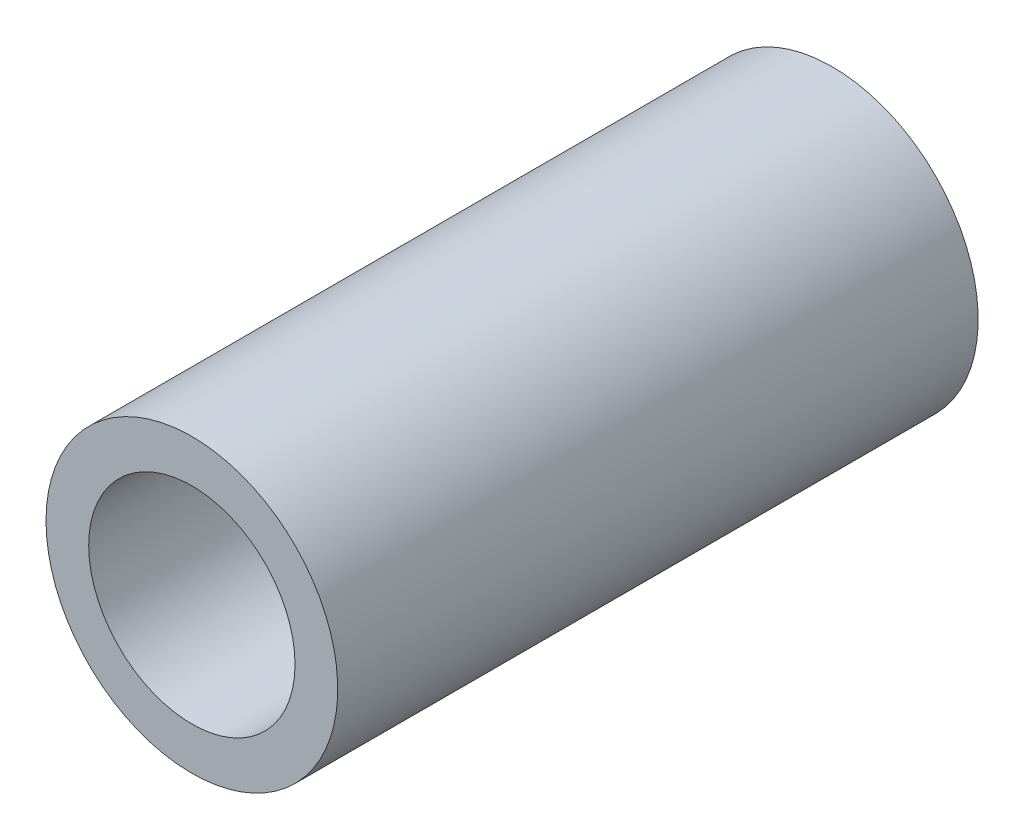
SolidWorks part; units mm, degrees
material "AISI 1020"
ref_plane "Plano frontal" through (0, 0, 0) normal (0, 0, 1) x (1, 0, 0)
ref_plane "Plano superior" through (0, 0, 0) normal (0, 1, 0) x (1, 0, 0)
ref_plane "Plano direito" through (0, 0, 0) normal (1, 0, 0) x (0, 0, -1)
sketch "Esboço1" plane through (0, 0, 0) normal (0, 0, 1) x (1, 0, 0)
  circle A0 centre (0, 0) radius 7.25
  circle A1 centre (0, 0) radius 10.25
  dimension "D1" = 14.5
  dimension "D2" = 20.5
extrude "Ressalto-extrusão1" add sketch "Esboço1" along normal mid plane 45
